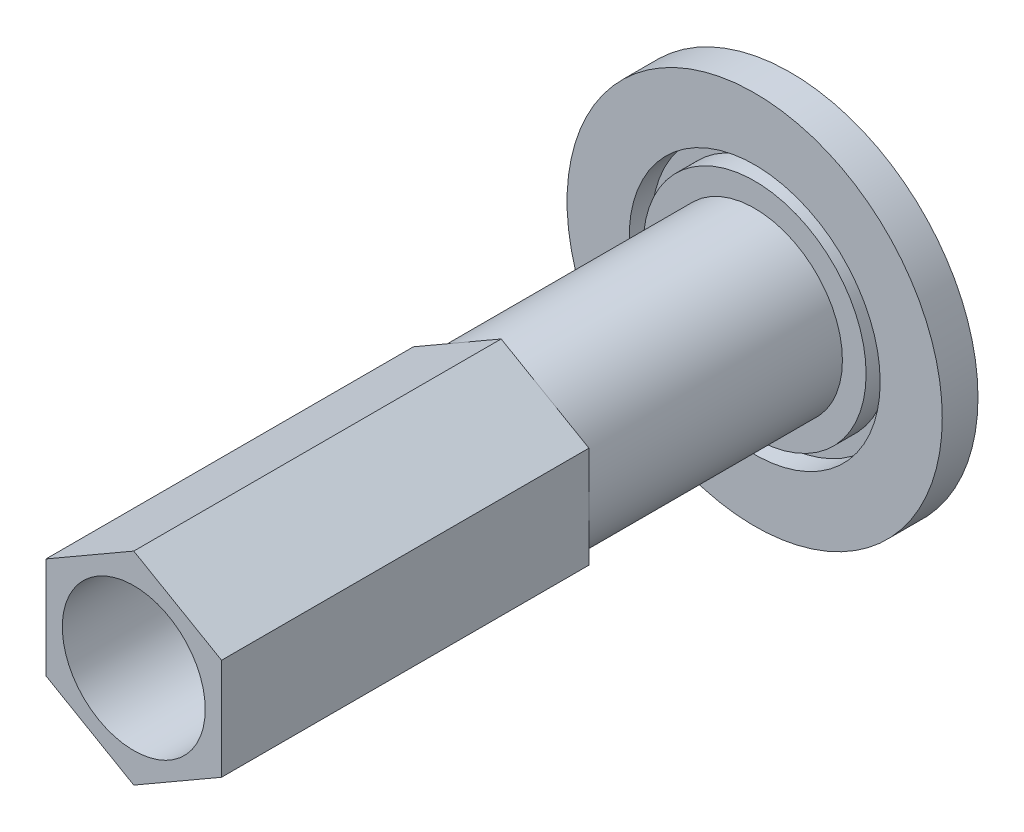
SolidWorks part; units mm, degrees
ref_plane "Front Plane" through (0, 0, 0) normal (0, 0, 1) x (1, 0, 0)
ref_plane "Top Plane" through (0, 0, 0) normal (0, 1, 0) x (1, 0, 0)
ref_plane "Right Plane" through (0, 0, 0) normal (1, 0, 0) x (0, 0, -1)
sketch "Sketch1" plane through (0, 0, 0) normal (0, 1, 0) x (1, 0, 0)
  line L0 (0, -39.84) -> (0, 48.538) construction
  line L1 (-48.4604, 0) -> (48.3051, 0) construction
  line L2 (0, 0) -> (16, 0)
  line L3 (16, 0) -> (16, -71)
  line L4 (16, -71) -> (19.65, -71)
  line L5 (19.65, -71) -> (19.65, 68)
  line L6 (19.65, 68) -> (24.95, 68)
  line L7 (24.95, 68) -> (24.95, 73)
  line L8 (24.95, 73) -> (28.1, 73)
  line L9 (28.1, 73) -> (28.1, 68)
  line L10 (28.1, 68) -> (42, 68)
  line L11 (42, 68) -> (42, 76)
  line L12 (42, 76) -> (16.65, 76)
  line L13 (16.65, 76) -> (16.65, 18.0044)
  line L14 (16.65, 18.0044) -> (12, 18.0044)
  line L15 (12, 18.0044) -> (12, 24.8827)
  line L16 (12, 24.8827) -> (0, 24.8827)
  line L17 (0, 0) -> (0, 24.8827)
  line L18 (22.5, -14.5339) -> (22.5, 92.6552) construction
  dimension "D1" = 42
  dimension "D2" = 8
  dimension "D3" = 16
  dimension "D4" = 19.65
  dimension "D5" = 71
  dimension "D6" = 68
  dimension "D7" = 5.3
  dimension "D8" = 3
  dimension "D9" = 3.15
  dimension "D10" = 68
  dimension "D11" = 5
  dimension "D12" = 12
  dimension "D13" = 22.5
revolve "Revolve1" add sketch "Sketch1" angle 360 about L0
sketch "Sketch2" plane through (0, 0, 71) normal (0, 0, 1) x (1, 0, 0)
  line L0 (0, 50.7794) -> (0, -52.6576) construction
  line L2 (0, 22.6899) -> (-19.65, 11.3449)
  line L3 (-19.65, 11.3449) -> (-19.65, -11.3449)
  line L4 (-19.65, -11.3449) -> (0, -22.6899)
  line L5 (0, -22.6899) -> (19.65, -11.3449)
  line L6 (19.65, -11.3449) -> (19.65, 11.3449)
  line L7 (19.65, 11.3449) -> (0, 22.6899)
  circle A0 centre (0, 0) radius 16
  circle A1 centre (0, 0) radius 19.65 construction
  dimension "D1" = 32
  dimension "D2" = 39.3
extrude "Boss-Extrude1" add sketch "Sketch2" against normal blind 82.25
